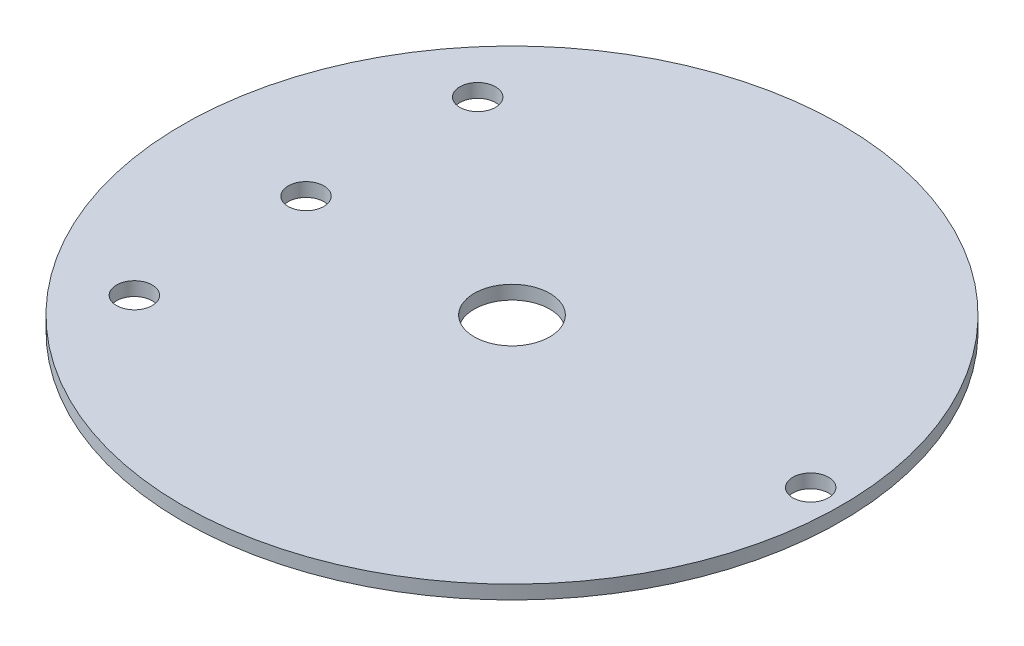
SolidWorks part; units mm, degrees
ref_plane "Front Plane" through (0, 0, 0) normal (0, 0, 1) x (1, 0, 0)
ref_plane "Top Plane" through (0, 0, 0) normal (0, 1, 0) x (1, 0, 0)
ref_plane "Right Plane" through (0, 0, 0) normal (1, 0, 0) x (0, 0, -1)
sketch "Sketch1" plane through (0, 0, 0) normal (0, 1, 0) x (1, 0, 0)
  line L0 (-30, -25) -> (-30, 25) construction
  line L1 (0, 0) -> (43.5, 0) construction
  circle A0 centre (0, 0) radius 48
  circle A1 centre (-30, 0) radius 2.6
  circle A2 centre (0, 0) radius 5.5
  circle A3 centre (-30, 25) radius 2.6
  circle A4 centre (-30, -25) radius 2.6
  circle A5 centre (43.5, 0) radius 2.6
  point P9 (-30, 0)
  dimension "D1" = 96
  dimension "D2" = 5.2
  dimension "D4" = 11
  dimension "D3" = 30
  dimension "D5" = 50
  dimension "D6" = 43.5
extrude "Boss-Extrude1" add sketch "Sketch1" along normal blind 2
